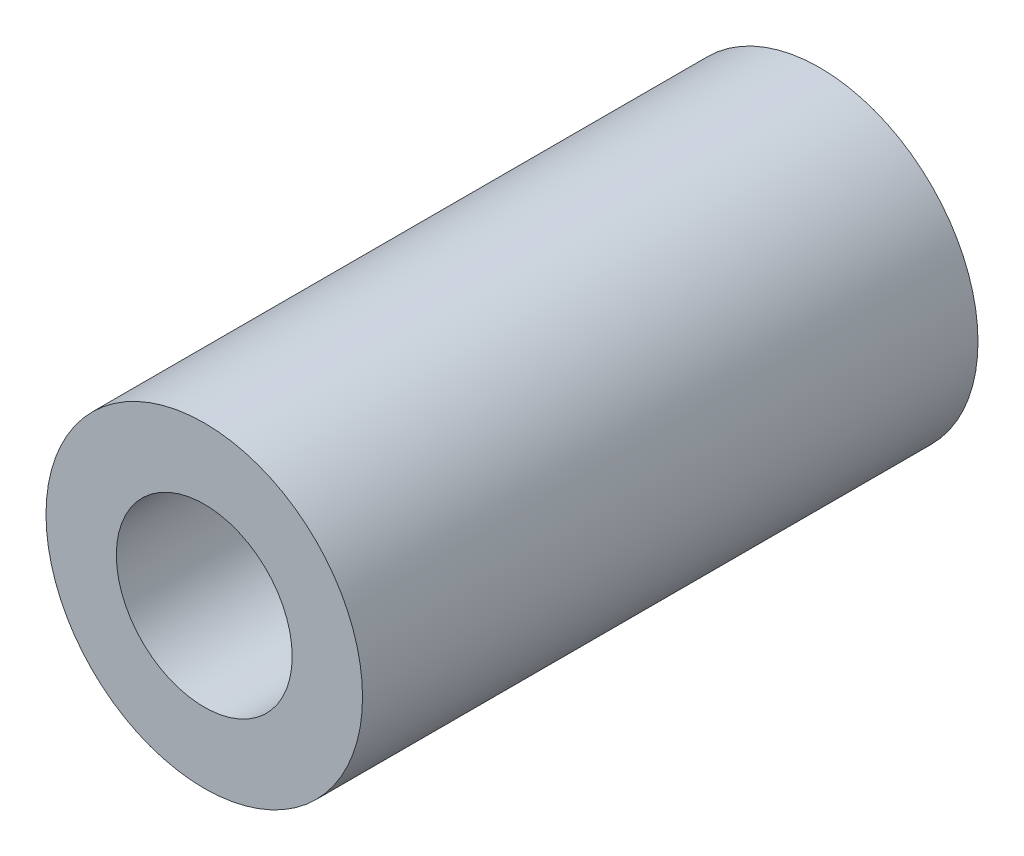
SolidWorks part; units mm, degrees
ref_plane "Plan de face" through (0, 0, 0) normal (0, 0, 1) x (1, 0, 0)
ref_plane "Plan de dessus" through (0, 0, 0) normal (0, 1, 0) x (1, 0, 0)
ref_plane "Plan de droite" through (0, 0, 0) normal (1, 0, 0) x (0, 0, -1)
sketch "Esquisse1" plane through (0, 0, 0) normal (0, 0, 1) x (1, 0, 0)
  circle A0 centre (0, 0) radius 9
  circle A1 centre (0, 0) radius 5
  dimension "D1" = 18
  dimension "D2" = 10
extrude "Boss.-Extru.1" add sketch "Esquisse1" along normal blind 35
